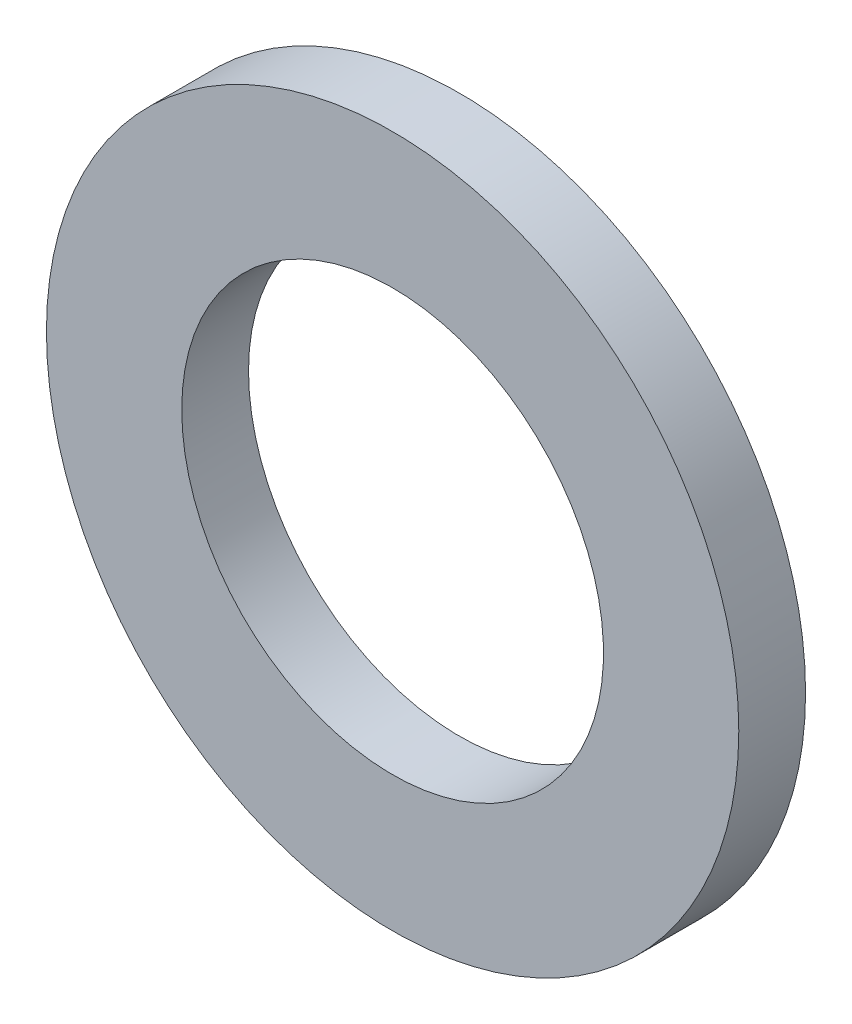
SolidWorks part; units mm, degrees
ref_plane "Front" through (0, 0, 0) normal (0, 0, 1) x (1, 0, 0)
ref_plane "Top" through (0, 0, 0) normal (0, 1, 0) x (1, 0, 0)
ref_plane "Right" through (0, 0, 0) normal (1, 0, 0) x (0, 0, -1)
sketch "Skizze1" plane through (0, 0, 0) normal (0, 0, 1) x (1, 0, 0)
  circle A0 centre (0, 0) radius 4.925
  circle A1 centre (0, 0) radius 3
  dimension "D1" = 9.85
  dimension "D2" = 6
extrude "Aufsatz-Linear austragen1" add sketch "Skizze1" along normal blind 0.95
